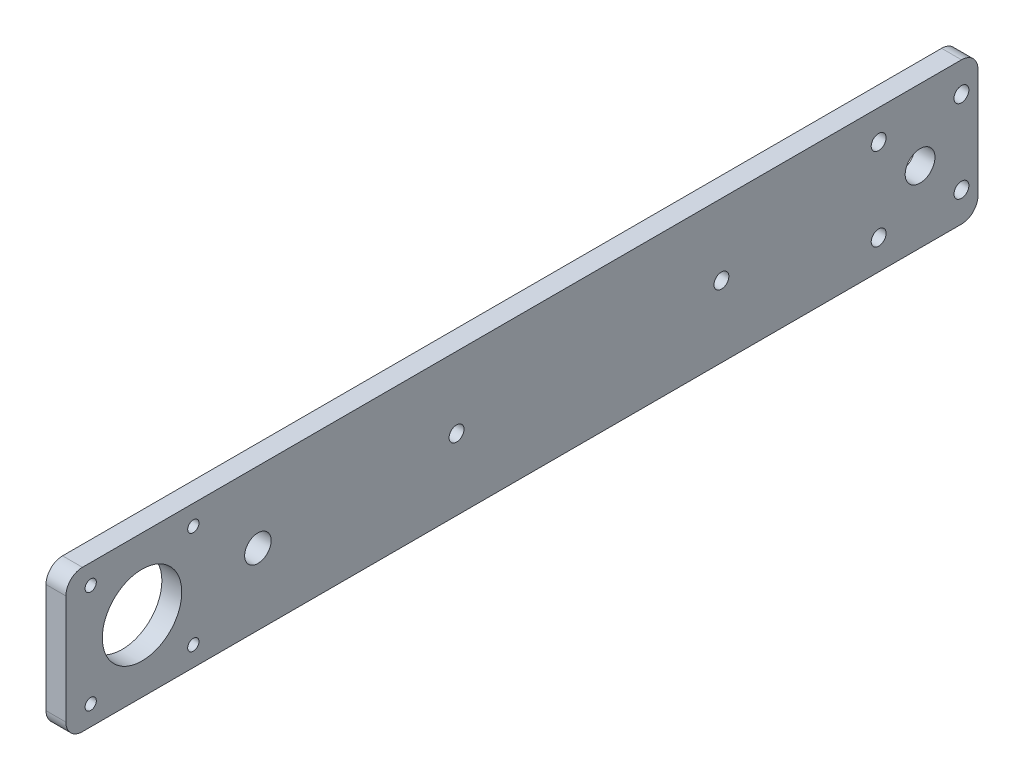
SolidWorks part; units mm, degrees
material "6061-T6 (SS)"
ref_plane "Alzado" through (0, 0, 0) normal (0, 0, 1) x (1, 0, 0)
ref_plane "Planta" through (0, 0, 0) normal (0, 1, 0) x (1, 0, 0)
ref_plane "Vista lateral" through (0, 0, 0) normal (1, 0, 0) x (0, 0, -1)
sketch "Croquis2" plane through (0, 0, 0) normal (1, 0, 0) x (0, 0, -1)
  line L2 (-100, 0) -> (100, 0) construction
  line L3 (-158, 21.5) -> (117.5, 21.5)
  line L5 (117.5, 21.5) -> (117.5, -21.5)
  line L6 (117.5, -21.5) -> (-158, -21.5)
  line L7 (-158, 21.5) -> (-158, -21.5)
  circle A2 centre (-100, 0) radius 4
  circle A3 centre (100, 0) radius 4.5
  circle A4 centre (-135, 0) radius 12
  point P4 (0, 0)
  point P7 (117.5, 0)
  dimension "D1" = 8
  dimension "D2" = 200
  dimension "D6" = 9
  dimension "D5" = 24
  dimension "D3" = 43
  dimension "D4" = 35
  dimension "D7" = 17.5
  dimension "D8" = 23
extrude "Saliente-Extruir1" add sketch "Croquis2" along normal mid plane 6
fillet "Redondeo1" radius 5 4 edges at (0, -21.5, -117.5) (0, 21.5, -117.5) (0, -21.5, 158) (0, 21.5, 158)
hole_wizard "Taladro de margen para M41" positions "Croquis5" profile "Croquis6" hole size "M4" standard "Ansi Metric" end condition up to next
sketch "Croquis5" plane through (3, 0, 0) normal (1, 0, 0) x (0, 0, -1)
  point P0 (112.5, 12.5)
  point P3 (112.5, -12.5)
  point P6 (87.5, -12.5)
  point P9 (87.5, 12.5)
sketch "Croquis6" plane through (3, 12.5, -112.5) normal (0, 1, 0) x (0, 0, -1)
  line L0 (0, 0) -> (0, 6)
  line L1 (0, 6) -> (2.25, 6)
  line L2 (2.25, 6) -> (2.25, 0)
  line L5 (2.25, 0) -> (0, 0)
  line L11 (0, -6.35) -> (0, 107.95) construction
  dimension "Diámetro de taladro hasta el siguiente" = 4.5
  dimension "Profundidad de taladro hasta el siguiente" = 6
hole_wizard "Taladro de margen para M31" positions "Croquis7" profile "Croquis8" hole size "M3" standard "Ansi Metric" end condition up to next
sketch "Croquis7" plane through (-3, 0, 0) normal (-1, 0, 0) x (0, 0, 1)
  point P0 (150.5, 15.5)
  point P3 (119.5, 15.5)
  point P6 (119.5, -15.5)
  point P9 (150.5, -15.5)
sketch "Croquis8" plane through (-3, 15.5, 150.5) normal (0, 1, 0) x (0, 0, 1)
  line L0 (0, 0) -> (0, 6)
  line L1 (0, 6) -> (1.7, 6)
  line L2 (1.7, 6) -> (1.7, 0)
  line L5 (1.7, 0) -> (0, 0)
  line L11 (0, -6.35) -> (0, 107.95) construction
  dimension "Diámetro de taladro hasta el siguiente" = 3.4
  dimension "Profundidad de taladro hasta el siguiente" = 6
hole_wizard "Taladro de margen para M42" positions "Croquis9" profile "Croquis10" hole size "M4" standard "Ansi Metric" end condition up to next
sketch "Croquis9" plane through (-3, 0, 0) normal (-1, 0, 0) x (0, 0, 1)
  point P0 (-40, 0)
  point P3 (40, 0)
sketch "Croquis10" plane through (-3, 0, -40) normal (0, 1, 0) x (0, 0, 1)
  line L0 (0, 0) -> (0, 6)
  line L1 (0, 6) -> (2.25, 6)
  line L2 (2.25, 6) -> (2.25, 0)
  line L5 (2.25, 0) -> (0, 0)
  line L11 (0, -6.35) -> (0, 107.95) construction
  dimension "Diámetro de taladro hasta el siguiente" = 4.5
  dimension "Profundidad de taladro hasta el siguiente" = 6
